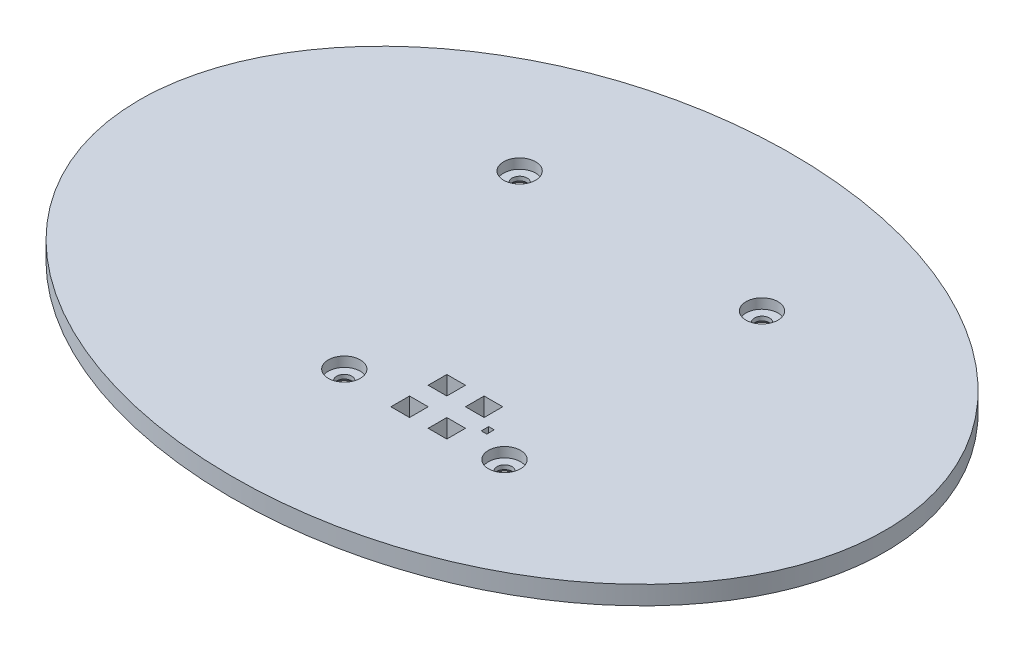
SolidWorks part; units mm, degrees
ref_plane "Front Plane" through (0, 0, 0) normal (0, 0, 1) x (1, 0, 0)
ref_plane "Top Plane" through (0, 0, 0) normal (0, 1, 0) x (1, 0, 0)
ref_plane "Right Plane" through (0, 0, 0) normal (1, 0, 0) x (0, 0, -1)
sketch "Sketch2" plane through (0, 0, 0) normal (0, 1, 0) x (1, 0, 0)
  ellipse E0 centre (0, 0) end of major axis (-50.8, 0) minor radius 38.1
  dimension "D1" = 50.8
  dimension "D2" = 38.1
extrude "top" add sketch "Sketch2" along normal blind 2.54
sketch "pcb size" plane through (0, 2.54, 0) normal (0, 1, 0) x (1, 0, 0)
  line L1 (20.32, -21.59) -> (-20.32, -21.59)
  line L2 (20.32, -21.59) -> (20.32, 21.59)
  line L3 (20.32, 21.59) -> (-20.32, 21.59)
  line L4 (-20.32, -21.59) -> (-20.32, 21.59)
  line L5 (20.32, -21.59) -> (-20.32, 21.59) construction
  line L6 (20.32, 21.59) -> (-20.32, -21.59) construction
  point P0 (0, 0)
  dimension "D1" = 43.18
sketch "Sketch4" plane through (0, 2.54, 0) normal (0, 1, 0) x (1, 0, 0)
  line L0 (20.32, -21.59) -> (20.32, 21.59) construction
  line L1 (10.16, -19.05) -> (7.62, -19.05)
  line L2 (10.16, -19.05) -> (10.16, -16.51)
  line L3 (10.16, -16.51) -> (7.62, -16.51)
  line L4 (7.62, -19.05) -> (7.62, -16.51)
  line L5 (20.32, -21.59) -> (-20.32, -21.59) construction
  line L7 (10.16, -13.97) -> (7.62, -13.97)
  line L8 (10.16, -13.97) -> (10.16, -11.43)
  line L9 (10.16, -11.43) -> (7.62, -11.43)
  line L10 (7.62, -13.97) -> (7.62, -11.43)
  line L11 (5.08, -16.51) -> (2.54, -16.51)
  line L12 (5.08, -16.51) -> (5.08, -19.05)
  line L13 (5.08, -19.05) -> (2.54, -19.05)
  line L14 (2.54, -16.51) -> (2.54, -19.05)
  line L15 (5.08, -13.97) -> (2.54, -13.97)
  line L16 (5.08, -13.97) -> (5.08, -11.43)
  line L17 (5.08, -11.43) -> (2.54, -11.43)
  line L18 (2.54, -13.97) -> (2.54, -11.43)
  line L19 (11.5379, -14.732) -> (12.2999, -14.732)
  line L20 (11.5379, -14.732) -> (11.5379, -15.748)
  line L21 (11.5379, -15.748) -> (12.2999, -15.748)
  line L22 (12.2999, -14.732) -> (12.2999, -15.748)
  dimension "D1" = 10.16
  dimension "D2" = 2.54
  dimension "D3" = 2.54
  dimension "D4" = 2.54
  dimension "D5" = 2.54
  dimension "D6" = 2.54
  dimension "D7" = 2.54
  dimension "D8" = 2.54
  dimension "D9" = 2.54
  dimension "D10" = 2.54
  dimension "D11" = 0.762
  dimension "D12" = 0.762
  dimension "D13" = 0.762
extrude "buttons and LED" cut sketch "Sketch4" against normal blind 2.54
hole_wizard "CBORE for #1 Pan Head Machine Screw1" positions "Sketch6" profile "Sketch5" counterbore size "#1" standard "ANSI Inch" end condition through all
sketch "Sketch6" plane through (0, 2.54, 0) normal (0, 1, 0) x (1, 0, 0)
  line L0 (20.32, -21.59) -> (-20.32, 21.59) construction
  line L1 (20.32, 21.59) -> (-20.32, -21.59) construction
  line L2 (-20.32, -21.59) -> (-20.32, 21.59) construction
  line L3 (20.32, -21.59) -> (20.32, 21.59) construction
  line L4 (20.32, -21.59) -> (-20.32, -21.59) construction
  point P0 (-5.08, -17.78)
  point P2 (16.51, -17.5419)
  point P6 (16.51, 17.5419)
  point P10 (-16.51, 17.5419)
  dimension "D1" = 3.81
  dimension "D2" = 3.81
  dimension "D3" = 3.81
  dimension "D4" = 15.24
  dimension "D5" = 3.81
sketch "Sketch5" plane through (-5.08, 2.54, 17.78) normal (1, 0, 0) x (0, 0, 1)
  line L0 (0, 0) -> (0, 2.54)
  line L1 (1.0287, 1.905) -> (1.6637, 2.54)
  line L2 (1.0287, 1.905) -> (1.0287, 1.3462)
  line L3 (1.0287, 1.3462) -> (2.1831, 1.3462)
  line L4 (2.1831, 1.3462) -> (2.1831, 0)
  line L5 (2.1831, 0) -> (0, 0)
  line L11 (0, -6.35) -> (0, 107.95) construction
  line L12 (1.6637, 2.54) -> (0, 2.54)
  line L13 (-1.0287, 1.905) -> (-1.6637, 2.54) construction
  dimension "Thru Hole Dia." = 2.0574
  dimension "Thru Hole Depth" = 2.54
  dimension "C'Bore Dia." = 4.3663
  dimension "C'Bore Depth" = 1.3462
  dimension "Far C'Sink Dia." = 3.3274
  dimension "Far C'Sink Angle" = 90
